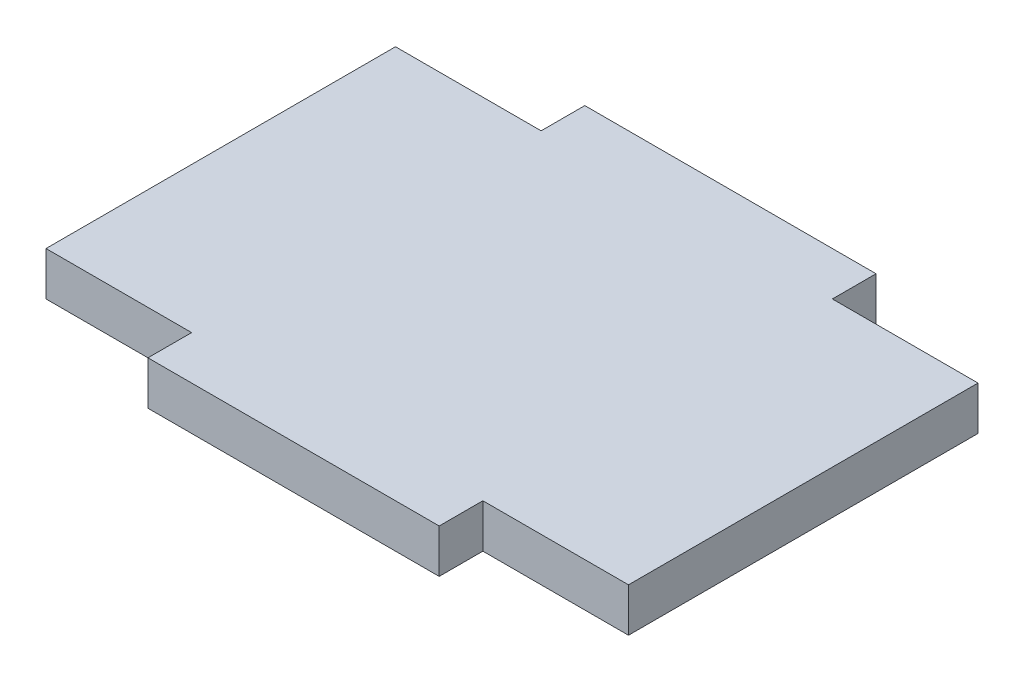
SolidWorks part; units mm, degrees
ref_plane "Front Plane" through (0, 0, 0) normal (0, 0, 1) x (1, 0, 0)
ref_plane "Top Plane" through (0, 0, 0) normal (0, 1, 0) x (1, 0, 0)
ref_plane "Right Plane" through (0, 0, 0) normal (1, 0, 0) x (0, 0, -1)
sketch "Sketch1" plane through (0, 0, 0) normal (0, 1, 0) x (1, 0, 0)
  line L0 (-10, 15) -> (10, 15)
  line L1 (10, 15) -> (10, 12)
  line L2 (10, 12) -> (20, 12)
  line L3 (20, 12) -> (20, -12)
  line L4 (20, -12) -> (10, -12)
  line L5 (10, -12) -> (10, -15)
  line L6 (10, -15) -> (-10, -15)
  line L7 (-10, -15) -> (-10, -12)
  line L8 (-10, -12) -> (-20, -12)
  line L9 (-20, -12) -> (-20, 12)
  line L10 (-20, 12) -> (-10, 12)
  line L11 (-10, 12) -> (-10, 15)
  point P2 (20, 0)
  point P13 (0, 15)
  dimension "D1" = 3
  dimension "D2" = 20
  dimension "D3" = 40
  dimension "D4" = 30
extrude "Boss-Extrude1" add sketch "Sketch1" along normal blind 3
